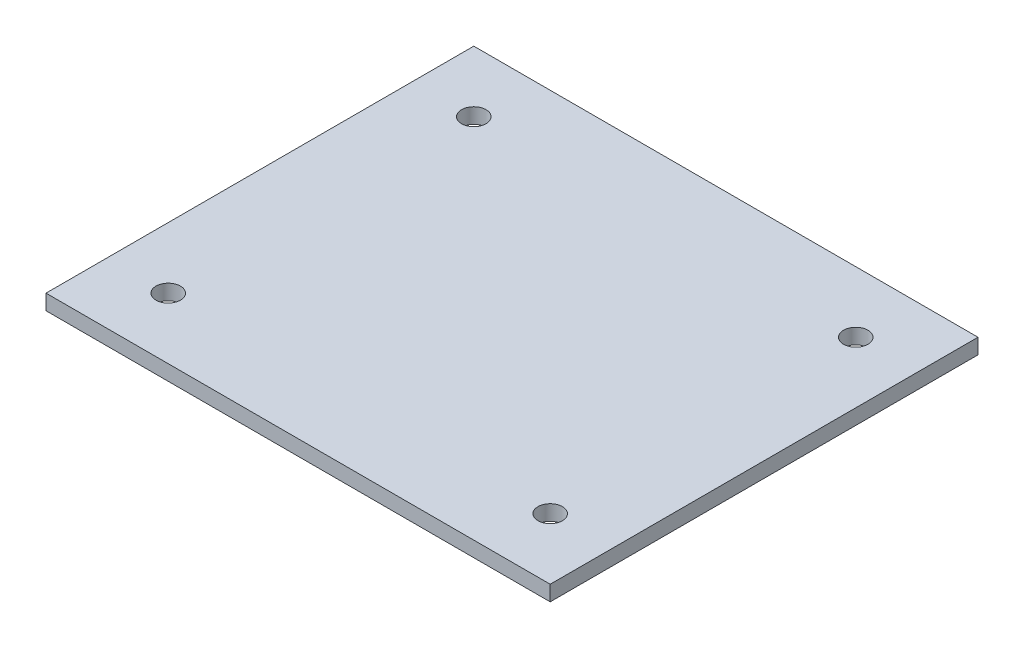
SolidWorks part; units mm, degrees
ref_plane "前视基准面" through (0, 0, 0) normal (0, 0, 1) x (1, 0, 0)
ref_plane "上视基准面" through (0, 0, 0) normal (0, 1, 0) x (1, 0, 0)
ref_plane "右视基准面" through (0, 0, 0) normal (1, 0, 0) x (0, 0, -1)
sketch "草图1" plane through (0, 0, 0) normal (0, 1, 0) x (1, 0, 0)
  line L1 (33, -28) -> (-33, -28)
  line L2 (33, -28) -> (33, 28)
  line L3 (33, 28) -> (-33, 28)
  line L4 (-33, -28) -> (-33, 28)
  line L5 (33, -28) -> (-33, 28) construction
  line L6 (33, 28) -> (-33, -28) construction
  point P0 (0, 0)
  dimension "D1" = 66
  dimension "D2" = 56
extrude "凸台-拉伸1" add sketch "草图1" along normal blind 2
sketch "草图2" plane through (0, 2, 0) normal (0, 1, 0) x (1, 0, 0)
  line L1 (25, -20) -> (-25, -20) construction
  line L2 (25, -20) -> (25, 20) construction
  line L3 (25, 20) -> (-25, 20) construction
  line L4 (-25, -20) -> (-25, 20) construction
  line L5 (25, -20) -> (-25, 20) construction
  line L6 (25, 20) -> (-25, -20) construction
  circle A0 centre (-25, 20) radius 1.6
  point P0 (0, 0)
  dimension "D3" = 3.2
  dimension "D1" = 50
  dimension "D2" = 40
extrude "切除-拉伸1" cut sketch "草图2" against normal blind 2
pattern_linear "阵列(线性)1" count 2 spacing 50 along (1, 0, 0) count 2 spacing 40 along (0, 0, 1) of "切除-拉伸1"
